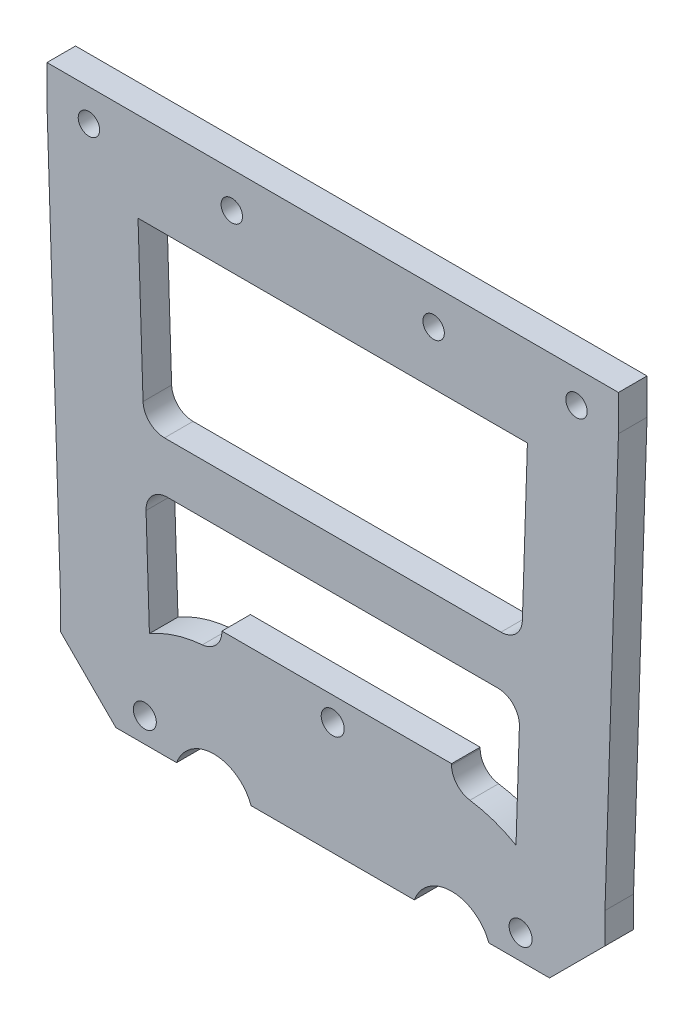
SolidWorks part; units mm, degrees
ref_plane "Front Plane" through (0, 0, 0) normal (0, 0, 1) x (1, 0, 0)
ref_plane "Top Plane" through (0, 0, 0) normal (0, 1, 0) x (1, 0, 0)
ref_plane "Right Plane" through (0, 0, 0) normal (1, 0, 0) x (0, 0, -1)
sketch "Sketch1" plane through (0, 0, 0) normal (0, 0, 1) x (1, 0, 0)
  line L3 (-38.1107, 1.6103) -> (-30.3544, -6.146)
  line L4 (-38.1107, 5.9045) -> (-38.1107, 1.6103)
  line L5 (30.3544, -6.146) -> (38.1107, 1.6103)
  line L6 (38.1107, 5.9045) -> (38.1107, 1.6103)
  line L7 (-30.3544, -6.146) -> (-21.8544, -6.146)
  line L8 (30.3544, -6.146) -> (21.8544, -6.146)
  line L9 (-11.4254, -6.146) -> (11.4254, -6.146)
  line L10 (0, 9.6619) -> (0, 69.6619) construction
  line L20 (40, 64.6619) -> (40, 69.6619)
  line L24 (40, 69.6619) -> (-40, 69.6619)
  line L26 (-40, 64.6619) -> (-40, 69.6619)
  line L27 (-40, 64.6619) -> (-38.1107, 5.9045)
  line L28 (38.1107, 5.9045) -> (40, 64.6619)
  line L29 (-27.2524, 57.1619) -> (-26.4556, 32.3819)
  line L30 (-25.6588, 7.602) -> (-25.6588, 7.602)
  line L31 (-25.6588, 7.602) -> (-25.6588, 7.602)
  line L32 (-25.6588, 7.602) -> (-25.6588, 7.602)
  line L34 (25.6588, 7.602) -> (25.6588, 7.602)
  line L35 (25.6588, 7.602) -> (25.6588, 7.602)
  line L36 (25.6588, 7.602) -> (25.6588, 7.602)
  line L37 (25.6588, 7.602) -> (26.2305, 25.3819)
  line L38 (27.2524, 57.1619) -> (27.2524, 57.1619)
  line L39 (27.2524, 57.1619) -> (-27.2524, 57.1619)
  line L40 (-27.2524, 57.1619) -> (-27.2524, 57.1619)
  line L41 (-26.4556, 32.3819) -> (26.4556, 32.3819)
  line L42 (-26.2305, 25.3819) -> (26.2305, 25.3819)
  line L43 (26.4556, 32.3819) -> (27.2524, 57.1619)
  line L44 (25.6588, 7.602) -> (27.2524, 57.1619) construction
  line L45 (-26.2305, 25.3819) -> (-25.6588, 7.602)
  line L46 (-27.2524, 57.1619) -> (-25.6588, 7.602) construction
  line L47 (-15.5116, 9.9826) -> (-15.5116, 12.9826)
  line L48 (-15.5116, 12.9826) -> (16.6399, 12.9826)
  line L49 (16.6399, 12.9826) -> (16.6399, 10.0179)
  line L51 (-5.7409, 6.354) -> (5.7409, 6.354) construction
  circle A8 centre (0, 9.6619) radius 1.6103
  circle A9 centre (-26.3017, -2.6839) radius 1.6103
  circle A10 centre (26.3017, -2.6839) radius 1.6103
  arc A11 (-11.4254, -6.146) -> (-21.8544, -6.146) centre (-16.6399, -8.0247) ccw
  arc A12 (21.8544, -6.146) -> (11.4254, -6.146) centre (16.6399, -8.0247) ccw
  circle A21 centre (34.1245, 65.1619) radius 1.5
  circle A23 centre (14.1245, 64.6619) radius 1.5
  circle A25 centre (-14.1245, 64.6619) radius 1.5
  circle A27 centre (-34.1245, 65.1619) radius 1.5
  arc A29 (-15.5116, 9.9826) -> (-25.6588, 7.602) centre (-16.6399, -8.0247) ccw
  arc A30 (25.6588, 7.602) -> (16.6399, 10.0179) centre (16.6399, -8.0247) ccw
  arc A31 (-5.7409, 6.354) -> (-25.6588, 7.602) centre (-16.6399, -8.0247) ccw construction
  arc A32 (25.6588, 7.602) -> (5.7409, 6.354) centre (16.6399, -8.0247) ccw construction
  point P2 (0, 69.6619)
  dimension "D1" = 8.5
  dimension "D2" = 8.5
  dimension "D3" = 60
  dimension "D4" = 12.5
  dimension "D5" = 7
  dimension "D6" = 3
extrude "Boss-Extrude1" add sketch "Sketch1" along normal blind 4
fillet "Fillet1" radius 3 6 edges at (-26.4556, 32.3819, 2) (26.4556, 32.3819, 2) (26.2305, 25.3819, 2) (-26.2305, 25.3819, 2) (-15.5116, 9.9826, 2) (16.6399, 10.0179, 2)
